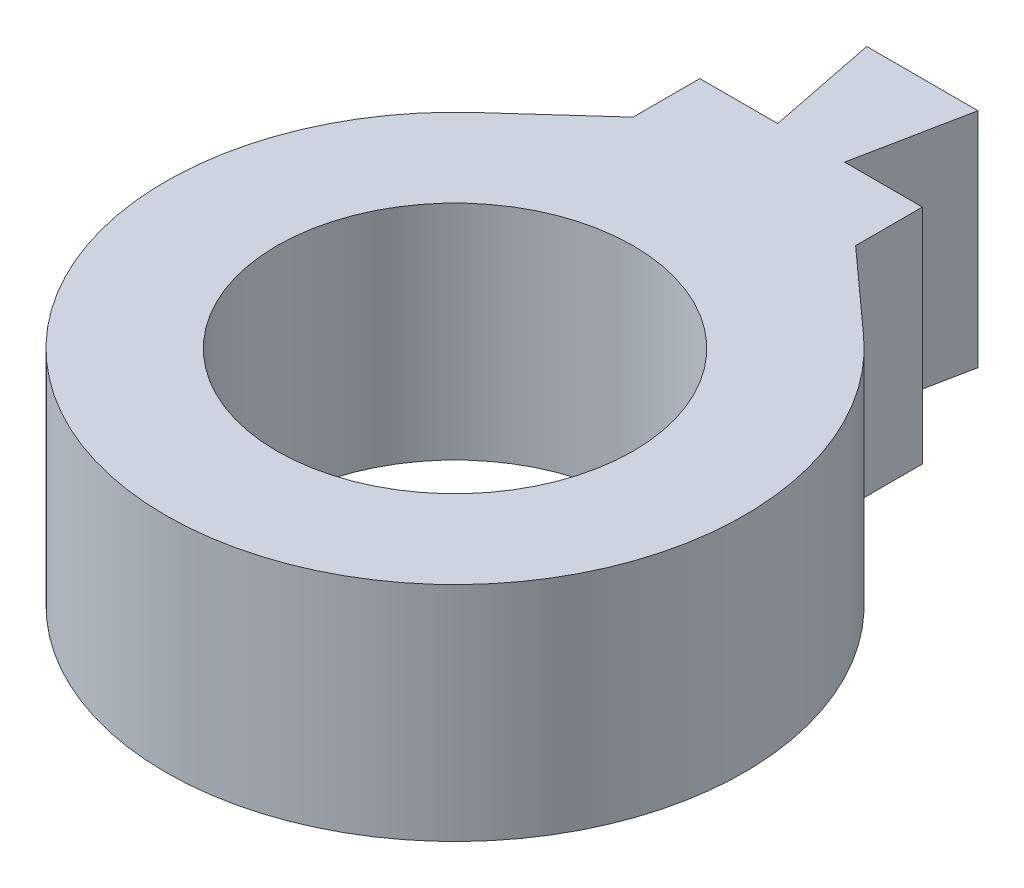
SolidWorks part; units mm, degrees
ref_plane "Front Plane" through (0, 0, 0) normal (0, 0, 1) x (1, 0, 0)
ref_plane "Top Plane" through (0, 0, 0) normal (0, 1, 0) x (1, 0, 0)
ref_plane "Right Plane" through (0, 0, 0) normal (1, 0, 0) x (0, 0, -1)
sketch "Sketch1" plane through (0, 0, 0) normal (0, 1, 0) x (1, 0, 0)
  line L0 (3.5, 0) -> (2.5, 5)
  line L1 (2.5, 5) -> (7.5, 5)
  line L2 (7.5, 5) -> (6.5, 0)
  line L3 (6.5, 0) -> (10, 0)
  line L4 (10, 0) -> (10, -3)
  line L5 (10, -3) -> (0, -3)
  line L6 (0, -3) -> (0, 0)
  line L7 (0, 0) -> (3.5, 0)
  line L8 (5, 5) -> (5, -3) construction
  line L9 (0, -3) -> (-3.7113, -6.3505)
  line L10 (10, -3) -> (13.7113, -6.3505)
  circle A0 centre (5, -16) radius 13
  circle A1 centre (5, -16) radius 8
  point P12 (0, 0)
  dimension "D8" = 16
  dimension "D1" = 10
  dimension "D2" = 5
  dimension "D3" = 5
  dimension "D4" = 3
  dimension "D5" = 3
  dimension "D6" = 1.5
  dimension "D7" = 5
extrude "Boss-Extrude1" add sketch "Sketch1" along normal blind 10 contours A0 A1 | A0 L10 L5 | L1 L8 L5 L4 L3 L2 | L8 L1 L0 L7 L6 L5 | A0 L5 L9
equation "\"D6@Sketch1\"=\"D4@Sketch1\"/2"
